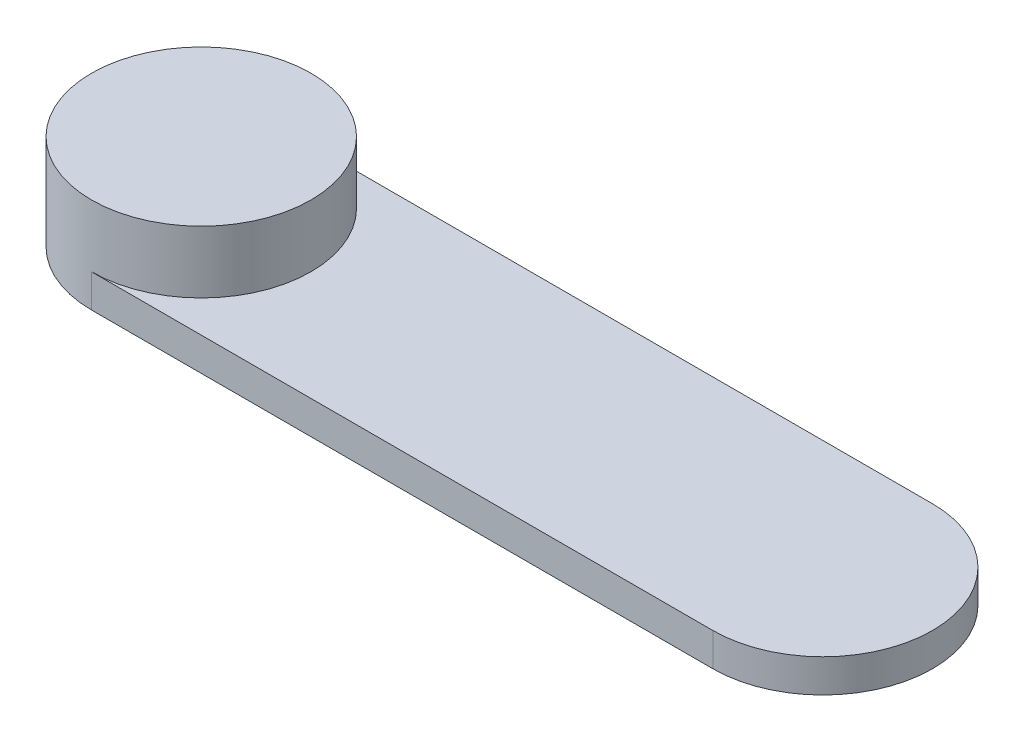
SolidWorks part; units mm, degrees
ref_plane "前视基准面" through (0, 0, 0) normal (0, 0, 1) x (1, 0, 0)
ref_plane "上视基准面" through (0, 0, 0) normal (0, 1, 0) x (1, 0, 0)
ref_plane "右视基准面" through (0, 0, 0) normal (1, 0, 0) x (0, 0, -1)
other "质心 (COM)"
sketch "草图1" plane through (0, 0, 0) normal (0, 1, 0) x (1, 0, 0)
  line L0 (75, 0) -> (-75, 0) construction
  line L1 (75, -26.5) -> (-75, -26.5)
  line L2 (75, 26.5) -> (-75, 26.5)
  arc A0 (75, -26.5) -> (75, 26.5) centre (75, 0) ccw
  arc A1 (-75, 26.5) -> (-75, -26.5) centre (-75, 0) ccw
  point P2 (0, 0)
  dimension "D1" = 26.5
  dimension "D2" = 150
extrude "凸台-拉伸1" add sketch "草图1" along normal blind 8
sketch "草图2" plane through (0, 8, 0) normal (0, 1, 0) x (1, 0, 0)
  arc A0 (-75, 26.5) -> (-75, -26.5) centre (-75, 0) ccw construction
  arc A1 (-75, 26.5) -> (-75, -26.5) centre (-75, 0) ccw construction
  circle A2 centre (-75, 0) radius 26.5
extrude "凸台-拉伸2" add sketch "草图2" along normal blind 15
